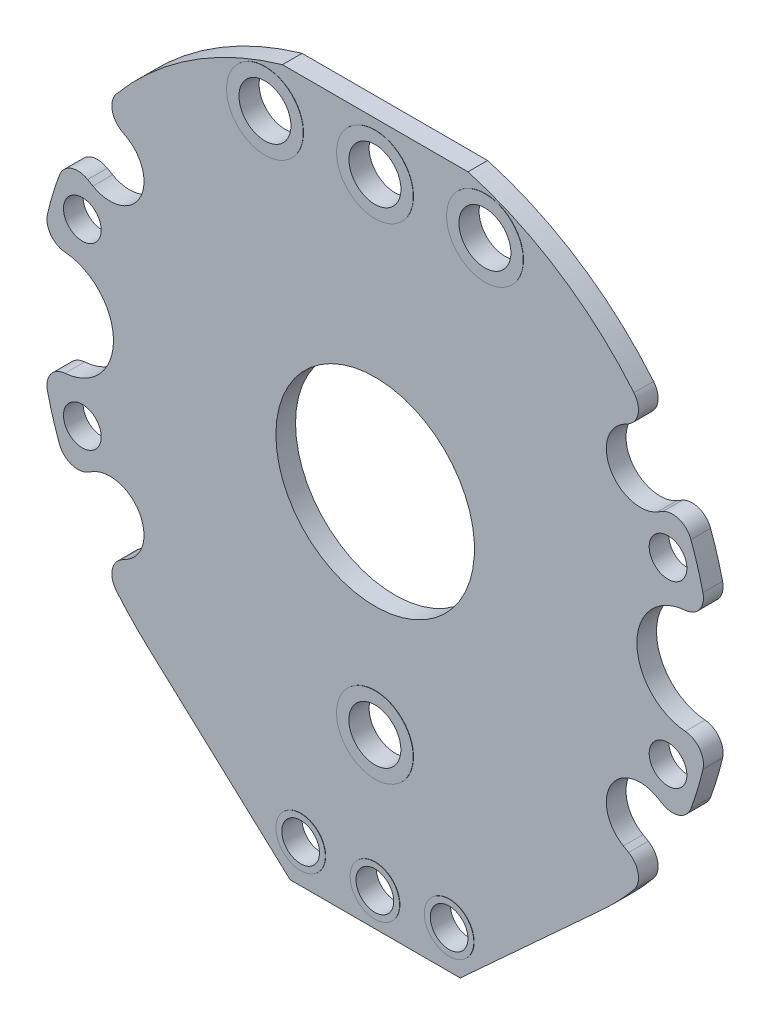
SolidWorks part; units mm, degrees
ref_plane "Front Plane" through (0, 0, 0) normal (0, 0, 1) x (1, 0, 0)
ref_plane "Top Plane" through (0, 0, 0) normal (0, 1, 0) x (1, 0, 0)
ref_plane "Right Plane" through (0, 0, 0) normal (1, 0, 0) x (0, 0, -1)
ref_plane "Plane4" through (0, 0, -0.7937) normal (0, 0, -1) x (-1, 0, 0)
sketch "Sketch1" plane through (0, 0, -0.7937) normal (0, 0, -1) x (-1, 0, 0)
  line L0 (-18.3768, -20.0548) -> (0, -36.8941)
  line L1 (0, -36.8941) -> (18.3768, -20.0548)
  line L2 (7.5, 26.1468) -> (-7.5, 26.1468)
  arc A0 (18.3768, -20.0548) -> (7.5, 26.1468) centre (0, 0) ccw
  arc A1 (-7.5, 26.1468) -> (-18.3768, -20.0548) centre (0, 0) ccw
  dimension "D1" = 15
  dimension "D2" = 26.1468
extrude "Boss-Extrude1" add sketch "Sketch1" against normal blind 1.5875
sketch "Sketch2" plane through (0, 0, 0.7937) normal (0, 0, 1) x (1, 0, 0)
  line L0 (-25.0713, 11.2995) -> (-22.8091, 9.9934)
  line L1 (-20.0591, 14.7566) -> (-22.3213, 16.0626)
  arc A0 (-22.3213, 16.0626) -> (-25.0713, 11.2995) centre (0, 0) ccw
  arc A1 (-22.8091, 9.9934) -> (-20.0591, 14.7566) centre (-21.4341, 12.375) ccw
extrude "Cut-Extrude1" cut sketch "Sketch2" against normal through all
sketch "Sketch3" plane through (0, 0, 0.7937) normal (0, 0, 1) x (1, 0, 0)
  line L0 (22.3213, 16.0626) -> (20.0591, 14.7566)
  line L1 (22.8091, 9.9934) -> (25.0713, 11.2995)
  arc A0 (25.0713, 11.2995) -> (22.3213, 16.0626) centre (0, 0) ccw
  arc A1 (20.0591, 14.7566) -> (22.8091, 9.9934) centre (21.4341, 12.375) ccw
extrude "Cut-Extrude2" cut sketch "Sketch3" against normal through all
sketch "Sketch4" plane through (0, 0, 0.7937) normal (0, 0, 1) x (1, 0, 0)
  line L0 (25.0713, -11.2995) -> (22.8091, -9.9934)
  line L1 (20.0591, -14.7566) -> (22.3213, -16.0626)
  arc A0 (22.3213, -16.0626) -> (25.0713, -11.2995) centre (0, 0) ccw
  arc A1 (22.8091, -9.9934) -> (20.0591, -14.7566) centre (21.4341, -12.375) ccw
extrude "Cut-Extrude3" cut sketch "Sketch4" against normal through all
sketch "Sketch5" plane through (0, 0, 0.7937) normal (0, 0, 1) x (1, 0, 0)
  line L0 (-22.3213, -16.0626) -> (-20.0591, -14.7566)
  line L1 (-22.8091, -9.9934) -> (-25.0713, -11.2995)
  arc A0 (-25.0713, -11.2995) -> (-22.3213, -16.0626) centre (0, 0) ccw
  arc A1 (-20.0591, -14.7566) -> (-22.8091, -9.9934) centre (-21.4341, -12.375) ccw
extrude "Cut-Extrude4" cut sketch "Sketch5" against normal through all
ref_plane "Plane5" through (0, -17, 0) normal (0, -1, 0) x (1, 0, 0)
sketch "Sketch6" plane through (0, -17, 0) normal (0, -1, 0) x (1, 0, 0)
  line L0 (3.0988, 0.8191) -> (0, 0.8192)
  line L1 (0, 0.8192) -> (0, 0.7937)
  line L2 (0, 0.7937) -> (3.0988, 0.7937)
  line L3 (3.0988, 0.7937) -> (3.0988, 0.8191)
  line L4 (0, 0.8192) -> (0, 0.7937) construction
revolve "Revolve1" add sketch "Sketch6" angle 360 about L4
ref_plane "Plane6" through (0, 17.78, 0) normal (0, -1, 0) x (1, 0, 0)
sketch "Sketch7" plane through (0, 17.78, 0) normal (0, -1, 0) x (1, 0, 0)
  line L0 (3.0988, 0.8191) -> (0, 0.8192)
  line L1 (0, 0.8192) -> (0, 0.7937)
  line L2 (0, 0.7937) -> (3.0988, 0.7937)
  line L3 (3.0988, 0.7937) -> (3.0988, 0.8191)
  line L4 (0, 0.8192) -> (0, 0.7937) construction
revolve "Revolve2" [suppressed] add sketch "Sketch7" angle 360 about L4
ref_plane "Plane7" through (0, -27.6013, 0) normal (0, -1, 0) x (1, 0, 0)
sketch "Sketch8" plane through (0, -27.6013, 0) normal (0, -1, 0) x (1, 0, 0)
  line L0 (-5.3958, 0.8191) -> (-7.3958, 0.8192)
  line L1 (-7.3958, 0.8192) -> (-7.3958, 0.7937)
  line L2 (-7.3958, 0.7937) -> (-5.3958, 0.7937)
  line L3 (-5.3958, 0.7937) -> (-5.3958, 0.8191)
  line L4 (-7.3958, 0.8192) -> (-7.3958, 0.7937) construction
revolve "Revolve3" [suppressed] add sketch "Sketch8" angle 360 about L4
sketch "Sketch9" plane through (0, -27.6013, 0) normal (0, -1, 0) x (1, 0, 0)
  line L0 (9.3958, 0.8191) -> (7.3958, 0.8192)
  line L1 (7.3958, 0.8192) -> (7.3958, 0.7937)
  line L2 (7.3958, 0.7937) -> (9.3958, 0.7937)
  line L3 (9.3958, 0.7937) -> (9.3958, 0.8191)
  line L4 (7.3958, 0.8192) -> (7.3958, 0.7937) construction
revolve "Revolve4" [suppressed] add sketch "Sketch9" angle 360 about L4
ref_plane "Plane8" through (0, -28.575, 0) normal (0, -1, 0) x (1, 0, 0)
sketch "Sketch10" plane through (0, -28.575, 0) normal (0, -1, 0) x (1, 0, 0)
  line L0 (2, 0.8191) -> (0, 0.8192)
  line L1 (0, 0.8192) -> (0, 0.7937)
  line L2 (0, 0.7937) -> (2, 0.7937)
  line L3 (2, 0.7937) -> (2, 0.8191)
  line L4 (0, 0.8192) -> (0, 0.7937) construction
revolve "Revolve5" add sketch "Sketch10" angle 360 about L4
ref_plane "Plane9" through (0, 16.4194, 0) normal (0, -1, 0) x (1, 0, 0)
sketch "Sketch11" plane through (0, 16.4194, 0) normal (0, -1, 0) x (1, 0, 0)
  line L0 (-3.7225, 0.8191) -> (-6.8213, 0.8192)
  line L1 (-6.8213, 0.8192) -> (-6.8213, 0.7937)
  line L2 (-6.8213, 0.7937) -> (-3.7225, 0.7937)
  line L3 (-3.7225, 0.7937) -> (-3.7225, 0.8191)
  line L4 (-6.8213, 0.8192) -> (-6.8213, 0.7937) construction
revolve "Revolve6" [suppressed] add sketch "Sketch11" angle 360 about L4
sketch "Sketch12" plane through (0, 16.4194, 0) normal (0, -1, 0) x (1, 0, 0)
  line L0 (9.9201, 0.8191) -> (6.8213, 0.8192)
  line L1 (6.8213, 0.8192) -> (6.8213, 0.7937)
  line L2 (6.8213, 0.7937) -> (9.9201, 0.7937)
  line L3 (9.9201, 0.7937) -> (9.9201, 0.8191)
  line L4 (6.8213, 0.8192) -> (6.8213, 0.7937) construction
revolve "Revolve7" [suppressed] add sketch "Sketch12" angle 360 about L4
sketch "Sketch15" plane through (0, -27.6013, 0) normal (0, -1, 0) x (1, 0, 0)
  line L0 (-5.3958, -0.7937) -> (-7.3958, -0.7937)
  line L1 (-7.3958, -0.7937) -> (-7.3958, -0.8192)
  line L2 (-7.3958, -0.8192) -> (-5.3958, -0.8191)
  line L3 (-5.3958, -0.8191) -> (-5.3958, -0.7937)
  line L4 (-7.3958, -0.7937) -> (-7.3958, -0.8192) construction
revolve "Revolve10" [suppressed] add sketch "Sketch15" angle 360 about L4
sketch "Sketch16" plane through (0, -27.6013, 0) normal (0, -1, 0) x (1, 0, 0)
  line L0 (9.3958, -0.7937) -> (7.3958, -0.7937)
  line L1 (7.3958, -0.7937) -> (7.3958, -0.8192)
  line L2 (7.3958, -0.8192) -> (9.3958, -0.8191)
  line L3 (9.3958, -0.8191) -> (9.3958, -0.7937)
  line L4 (7.3958, -0.7937) -> (7.3958, -0.8192) construction
revolve "Revolve11" [suppressed] add sketch "Sketch16" angle 360 about L4
hole_wizard "M14 Clearance Hole1" positions "Sketch21" profile "Sketch20" hole size "M14" standard "ANSI Metric"
sketch "Sketch21" plane through (0, 0, -0.7937) normal (0, 0, -1) x (-1, 0, 0)
  point P0 (0, 0)
sketch "Sketch20" plane through (0, 0, -0.7937) normal (1, 0, 0) x (0, 1, 0)
  line L0 (0, 0) -> (0, 1.6129)
  line L1 (0, 1.6129) -> (8.025, 1.6129)
  line L2 (8.025, 1.6129) -> (8.025, 0)
  line L5 (8.025, 0) -> (0, 0)
  line L11 (0, -6.35) -> (0, 107.95) construction
  dimension "Thru Hole Dia." = 16.05
  dimension "Thru Hole Depth" = 1.6129
hole_wizard "Ø8.5 (8.5) Diameter Hole1" positions "Sketch23" profile "Sketch22" hole size "Ø8.5" standard "ANSI Metric"
sketch "Sketch23" plane through (0, 0, 0.7937) normal (0, 0, 1) x (1, 0, 0)
  point P0 (-25.4, 0)
sketch "Sketch22" plane through (-25.4, 0, 0.7937) normal (1, 0, 0) x (0, -1, 0)
  line L0 (0, 0) -> (0, 1.5875)
  line L1 (0, 1.5875) -> (4.25, 1.5875)
  line L2 (4.25, 1.5875) -> (4.25, 0)
  line L5 (4.25, 0) -> (0, 0)
  line L11 (0, -6.35) -> (0, 107.95) construction
  dimension "Thru Hole Dia." = 8.5
  dimension "Thru Hole Depth" = 1.5875
hole_wizard "Ø8.5 (8.5) Diameter Hole2" positions "Sketch25" profile "Sketch24" hole size "Ø8.5" standard "ANSI Metric"
sketch "Sketch25" plane through (0, 0, -0.7937) normal (0, 0, -1) x (-1, 0, 0)
  point P0 (-25.4, 0)
sketch "Sketch24" plane through (25.4, 0, -0.7937) normal (1, 0, 0) x (0, 1, 0)
  line L0 (0, 0) -> (0, 1.6129)
  line L1 (0, 1.6129) -> (4.25, 1.6129)
  line L2 (4.25, 1.6129) -> (4.25, 0)
  line L5 (4.25, 0) -> (0, 0)
  line L11 (0, -6.35) -> (0, 107.95) construction
  dimension "Thru Hole Dia." = 8.5
  dimension "Thru Hole Depth" = 1.6129
sketch "Sketch17" plane through (0, -28.575, 0) normal (0, -1, 0) x (1, 0, 0)
  line L0 (2, -0.7937) -> (0, -0.7937)
  line L1 (0, -0.7937) -> (0, -0.8192)
  line L2 (0, -0.8192) -> (2, -0.8191)
  line L3 (2, -0.8191) -> (2, -0.7937)
  line L4 (0, -0.7937) -> (0, -0.8192) construction
revolve "Revolve12" add sketch "Sketch17" angle 360 about L4
hole_wizard "M2.5 Clearance Hole1" positions "Sketch27" profile "Sketch26" hole size "M2.5" standard "ANSI Metric" end condition through all
sketch "Sketch27" plane through (0, 0, -0.8191) normal (0, 0, -1) x (-1, 0, 0)
  point P0 (0, -27.9)
  point P1 (-6, -27.5)
  point P2 (6, -27.5)
  point P3 (23.6685, 7.2362)
  point P4 (23.6685, -7.2362)
  point P5 (-23.6685, -7.2362)
  point P6 (-23.6685, 7.2362)
  dimension "D1" = 27.5
  dimension "D2" = 27.9
  dimension "D3" = 6
  dimension "D4" = 6
sketch "Sketch26" plane through (0, -27.9, -0.8191) normal (1, 0, 0) x (0, 1, 0)
  line L0 (0, 0) -> (0, 1.6383)
  line L1 (0, 1.6383) -> (1.524, 1.6383)
  line L2 (1.524, 1.6383) -> (1.524, 0)
  line L5 (1.524, 0) -> (0, 0)
  line L11 (0, -6.35) -> (0, 107.95) construction
  dimension "Thru Hole Dia." = 3.048
  dimension "Thru Hole Depth" = 1.6383
hole_wizard "M3.5 Clearance Hole1" positions "Sketch29" profile "Sketch28" hole size "M3.5" standard "ANSI Metric" end condition through all
sketch "Sketch29" plane through (0, 0, -0.7937) normal (0, 0, -1) x (-1, 0, 0)
  point P0 (-8.89, 22.225)
  point P1 (8.89, 22.225)
  point P2 (0, 22.225)
  point P3 (0, -17)
sketch "Sketch28" plane through (8.89, 22.225, -0.7937) normal (1, 0, 0) x (0, 1, 0)
  line L0 (0, 0) -> (0, 1.6129)
  line L1 (0, 1.6129) -> (2.1, 1.6129)
  line L2 (2.1, 1.6129) -> (2.1, 0)
  line L5 (2.1, 0) -> (0, 0)
  line L11 (0, -6.35) -> (0, 107.95) construction
  dimension "Thru Hole Dia." = 4.2
  dimension "Thru Hole Depth" = 1.6129
sketch "Sketch13" plane through (0, -17, 0) normal (0, -1, 0) x (1, 0, 0)
  line L0 (3.0988, -0.7937) -> (0, -0.7937)
  line L1 (0, -0.7937) -> (0, -0.8192)
  line L2 (0, -0.8192) -> (3.0988, -0.8191)
  line L3 (3.0988, -0.8191) -> (3.0988, -0.7937)
  line L4 (0, -0.7937) -> (0, -0.8192) construction
revolve "Revolve8" [suppressed] add sketch "Sketch13" angle 360 about L4
sketch "Sketch18" plane through (0, 16.4194, 0) normal (0, -1, 0) x (1, 0, 0)
  line L0 (-3.7225, -0.7937) -> (-6.8213, -0.7937)
  line L1 (-6.8213, -0.7937) -> (-6.8213, -0.8192)
  line L2 (-6.8213, -0.8192) -> (-3.7225, -0.8191)
  line L3 (-3.7225, -0.8191) -> (-3.7225, -0.7937)
  line L4 (-6.8213, -0.7937) -> (-6.8213, -0.8192) construction
revolve "Revolve13" [suppressed] add sketch "Sketch18" angle 360 about L4
sketch "Sketch14" plane through (0, 17.78, 0) normal (0, -1, 0) x (1, 0, 0)
  line L0 (3.0988, -0.7937) -> (0, -0.7937)
  line L1 (0, -0.7937) -> (0, -0.8192)
  line L2 (0, -0.8192) -> (3.0988, -0.8191)
  line L3 (3.0988, -0.8191) -> (3.0988, -0.7937)
  line L4 (0, -0.7937) -> (0, -0.8192) construction
revolve "Revolve9" [suppressed] add sketch "Sketch14" angle 360 about L4
chamfer "Chamfer1" distance 9.3243 angle 42.5 1 edges at (0, -36.8941, 0)
fillet "Fillet1" radius 1.5875 12 edges at (-26.9095, 3.9729, 0) (-26.9095, -3.9729, 0) (-24.8112, -11.1493, 0) (-22.0612, -15.9125, 0) (-22.0612, 15.9125, 0) (-24.8112, 11.1493, 0) (22.0612, 15.9125, 0) (24.8112, 11.1493, 0) (26.9095, -3.9729, 0) (26.9095, 3.9729, 0) (24.8112, -11.1493, 0) (22.0612, -15.9125, 0)
sketch "Sketch30" plane through (0, 0, 0.7937) normal (0, 0, 1) x (1, 0, 0)
  circle A0 centre (-8.89, 22.225) radius 3.1
  circle A1 centre (0, 22.225) radius 3.1
  circle A2 centre (8.89, 22.225) radius 3.1
  circle A3 centre (8.89, 22.225) radius 2.1 construction
  circle A4 centre (0, 22.225) radius 2.1 construction
  circle A5 centre (-8.89, 22.225) radius 2.1 construction
  circle A6 centre (8.89, 22.225) radius 2.1
  circle A7 centre (0, 22.225) radius 2.1
  circle A8 centre (-8.89, 22.225) radius 2.1
  dimension "D1" = 6.2
extrude "Boss-Extrude2" add sketch "Sketch30" along normal blind 0.02
mirror "Mirror1" about plane through (0, 0, 0) normal (0, 0, 1) of "Boss-Extrude2"
sketch "Sketch31" plane through (0, 0, 0.7937) normal (0, 0, 1) x (1, 0, 0)
  circle A0 centre (-6.858, 16.51) radius 2.025
  circle A1 centre (0, 16.8813) radius 2.025
  circle A2 centre (6.858, 16.51) radius 2.025
  circle A3 centre (0, 16.8813) radius 1.525
  circle A4 centre (-6.858, 16.51) radius 1.525
  circle A5 centre (6.858, 16.51) radius 1.525
  dimension "D1" = 3.05
  dimension "D2" = 0.5
extrude "Boss-Extrude3" [suppressed] add sketch "Sketch31" along normal blind 0.0207
sketch "Sketch32" [suppressed] plane through (0, 0, 0.7937) normal (0, 0, 1) x (1, 0, 0)
  circle A1 centre (6.858, 16.51) radius 1.525 construction
  circle A2 centre (0, 16.8813) radius 1.525 construction
  circle A3 centre (-6.858, 16.51) radius 1.525 construction
  circle A4 centre (6.858, 16.51) radius 1.525
  circle A5 centre (0, 16.8813) radius 1.525
  circle A6 centre (-6.858, 16.51) radius 1.525
extrude "Cut-Extrude6" [suppressed] cut sketch "Sketch32" against normal through all
mirror "Mirror2" [suppressed] about plane through (0, 0, 0) normal (0, 0, 1)
sketch "Sketch33" plane through (0, 0, 0.7937) normal (0, 0, 1) x (1, 0, 0)
  line L1 (-7.3512, -28.9746) -> (-7.1679, -29.1425) construction
  line L2 (-6.8746, -30.5947) -> (-18.3768, -20.0548) construction
  circle A0 centre (-6, -27.5) radius 2
  circle A1 centre (6, -27.5) radius 2
  circle A2 centre (0, -28.575) radius 2 construction
  circle A3 centre (6, -27.5) radius 1.524 construction
  circle A4 centre (-6, -27.5) radius 1.524 construction
  circle A5 centre (6, -27.5) radius 1.524
  circle A6 centre (-6, -27.5) radius 1.524
extrude "Boss-Extrude4" add sketch "Sketch33" along normal up to surface (0.0254 mm away) up to face at (-2.1, -17, 0.8191)
sketch "Sketch34" plane through (0, 0, 0.8191) normal (0, 0, -1) x (-1, 0, 0)
  circle A0 centre (0, -28.575) radius 2
  circle A1 centre (0, -28.575) radius 2 construction
extrude "Cut-Extrude8" cut sketch "Sketch34" along normal up to surface (0.0254 mm away) up to face at (-8, -27.5, 0.7938)
sketch "Sketch36" plane through (0, 0, -0.8191) normal (0, 0, -1) x (-1, 0, 0)
  circle A2 centre (0, -28.575) radius 2
  circle A3 centre (0, -28.575) radius 2 construction
extrude "Cut-Extrude9" cut sketch "Sketch36" against normal up to surface (0.0254 mm away) up to face at (5.79, 22.225, -0.7937)
sketch "Sketch37" plane through (0, 0, 0.7937) normal (0, 0, 1) x (1, 0, 0)
  circle A0 centre (0, -27.9) radius 2
  circle A1 centre (-6, -27.5) radius 2 construction
  circle A2 centre (0, -27.9) radius 1.524 construction
  circle A3 centre (0, -27.9) radius 1.524
extrude "Boss-Extrude5" add sketch "Sketch37" along normal up to surface (0.0254 mm away) up to face at (-4.476, -27.5, 0.8191)
sketch "Sketch38" plane through (0, 0, -0.7937) normal (0, 0, -1) x (-1, 0, 0)
  circle A0 centre (0, -27.9) radius 2
  circle A1 centre (6, -27.5) radius 2
  circle A2 centre (-6, -27.5) radius 2
  circle A3 centre (0, -27.9) radius 2 construction
  circle A4 centre (6, -27.5) radius 1.524 construction
  circle A5 centre (0, -27.9) radius 1.524 construction
  circle A6 centre (-6, -27.5) radius 1.524 construction
  circle A7 centre (6, -27.5) radius 1.524
  circle A8 centre (0, -27.9) radius 1.524
  circle A9 centre (-6, -27.5) radius 1.524
extrude "Boss-Extrude6" add sketch "Sketch38" along normal up to surface (0.02 mm away) up to face at (10.99, 22.225, -0.8137)
sketch "Sketch39" plane through (0, 0, -0.7937) normal (0, 0, -1) x (-1, 0, 0)
  circle A0 centre (0, -17) radius 3.0988
  circle A1 centre (0, -17) radius 3.0988 construction
  circle A2 centre (0, -17) radius 2.1 construction
  circle A3 centre (0, -17) radius 2.1
extrude "Boss-Extrude7" add sketch "Sketch39" along normal blind 0.0207
